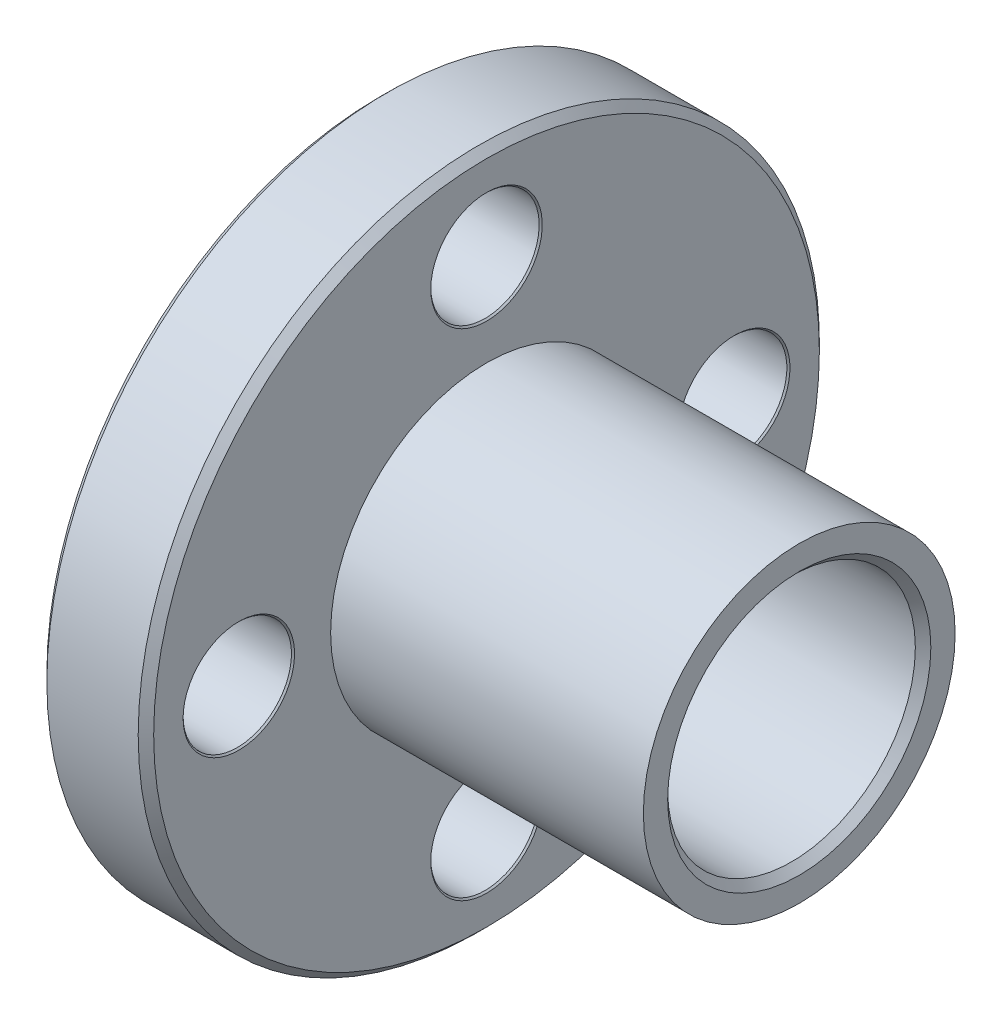
SolidWorks part; units mm, degrees
material "Aluminum Bronze"
ref_plane "Front Plane" through (0, 0, 0) normal (0, 0, 1) x (1, 0, 0)
ref_plane "Top Plane" through (0, 0, 0) normal (0, 1, 0) x (1, 0, 0)
ref_plane "Right Plane" through (0, 0, 0) normal (1, 0, 0) x (0, 0, -1)
sketch "Sketch1" plane through (0, 0, 0) normal (0, 0, 1) x (1, 0, 0)
  line L0 (-7.525, 0) -> (7.525, 0) construction
  line L1 (7.525, 0) -> (7.525, 5.035)
  line L2 (7.525, 5.035) -> (-2.575, 5.035)
  line L3 (-2.575, 5.035) -> (-2.575, 11)
  line L4 (-2.575, 11) -> (-6.025, 11)
  line L5 (-6.025, 11) -> (-6.025, 5.035)
  line L6 (-6.025, 5.035) -> (-7.525, 5.035)
  line L7 (-7.525, 5.035) -> (-7.525, 0)
  line L8 (-7.525, 0) -> (7.525, 0)
  dimension "D1" = 15.05
  dimension "D2" = 1.5
  dimension "D3" = 10.1
  dimension "D4" = 11
  dimension "D5" = 5.035
revolve "Revolve1" add sketch "Sketch1" angle 360 about L0
sketch "Sketch2" plane through (-7.525, 0, 0) normal (-1, 0, 0) x (0, 0, 1)
  point P0 (0, 0)
hole_wizard "Ø8.0 (8) Diameter Hole1" positions "3DSketch1" profile "Sketch3" hole size "Ø8.0" standard "ANSI Metric" end condition through all
sketch3d "3DSketch1"
  point P0 (-7.525, 0, 0)
sketch "Sketch3" plane through (-7.525, 0, 0) normal (0, 1, 0) x (0, 0, 1)
  line L0 (0, 0) -> (0, 15.05)
  line L1 (0, 15.05) -> (4.25, 15.05)
  line L2 (4, 14.8) -> (4, 0.25)
  line L3 (4, 0.25) -> (4.25, 0)
  line L5 (4.25, 0) -> (0, 0)
  line L6 (-4, 0.25) -> (-4.25, 0) construction
  line L7 (4.25, 15.05) -> (4, 14.8)
  line L8 (-4.25, 15.05) -> (-4, 14.8) construction
  line L11 (0, -6.35) -> (0, 107.95) construction
  dimension "Thru Hole Dia." = 8
  dimension "Thru Hole Depth" = 15.05
  dimension "Near C'Sink Dia." = 8.5
  dimension "Near C'Sink Angle" = 90
  dimension "Far C'Sink Dia." = 8.5
  dimension "Far C'Sink Angle" = 90
sketch "Sketch5" plane through (-6.025, 0, 0) normal (-1, 0, 0) x (0, 0, 1)
  circle A0 centre (0, 0) radius 8 construction
  point P3 (0, 8)
  point P4 (8, 0)
  point P5 (0, -8)
  point P6 (-8, 0)
  dimension "D1" = 16
hole_wizard "Ø3.5 (3.5) Diameter Hole1" positions "3DSketch2" profile "Sketch7" hole size "Ø3.5" standard "ANSI Metric" end condition up to next
sketch3d "3DSketch2"
  point P0 (-6.025, 8, 0)
  point P3 (-6.025, 0, 8)
  point P6 (-6.025, -8, 0)
  point P9 (-6.025, 0, -8)
sketch "Sketch7" plane through (-6.025, 8, 0) normal (0, 1, 0) x (0, 0, 1)
  line L0 (0, 0) -> (0, 3.45)
  line L1 (0, 3.45) -> (1.8, 3.45)
  line L2 (1.75, 3.4) -> (1.75, 0.05)
  line L3 (1.75, 0.05) -> (1.8, 0)
  line L5 (1.8, 0) -> (0, 0)
  line L6 (-1.75, 0.05) -> (-1.8, 0) construction
  line L7 (1.8, 3.45) -> (1.75, 3.4)
  line L8 (-1.8, 3.45) -> (-1.75, 3.4) construction
  line L11 (0, -6.35) -> (0, 107.95) construction
  dimension "Thru Hole Dia." = 3.5
  dimension "Thru Hole Depth" = 3.45
  dimension "Near C'Sink Dia." = 3.6
  dimension "Near C'Sink Angle" = 90
  dimension "Far C'Sink Dia." = 3.6
  dimension "Far C'Sink Angle" = 90
chamfer "Chamfer1" distance 0.25 angle 45 2 edges at (-2.575, 0, 11) (-6.025, 0, 11)
